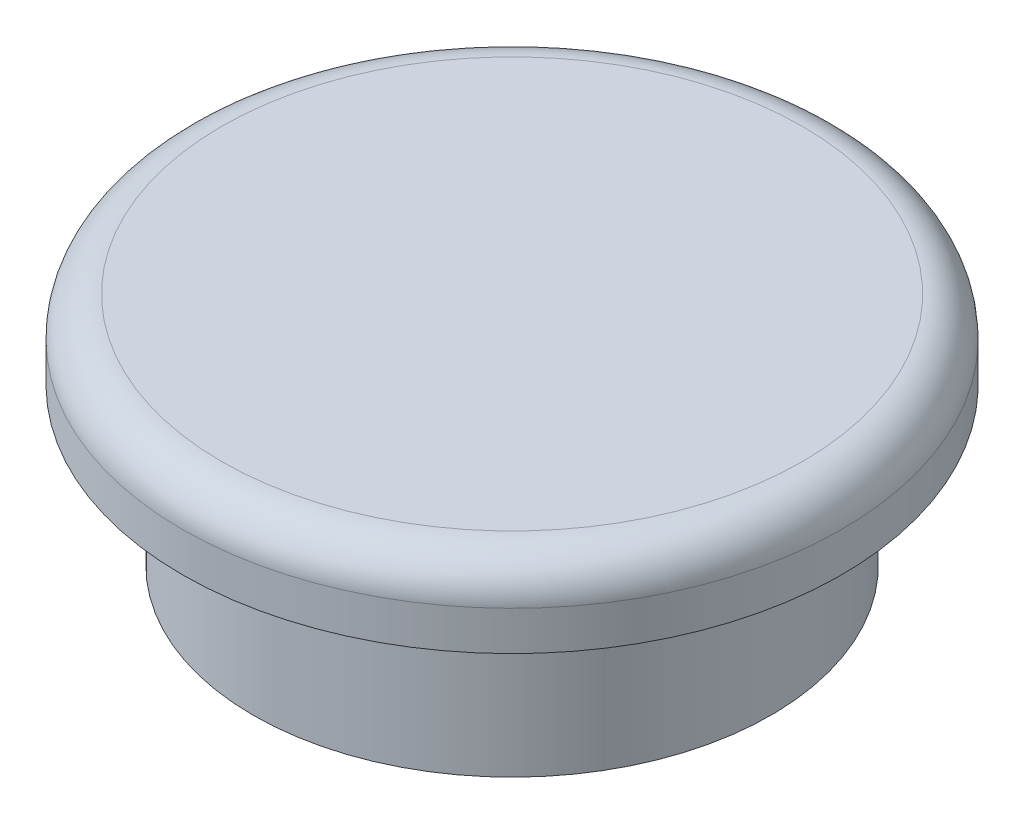
SolidWorks part; units mm, degrees
ref_plane "Front" through (0, 0, 0) normal (0, 0, 1) x (1, 0, 0)
ref_plane "Top" through (0, 0, 0) normal (0, 1, 0) x (1, 0, 0)
ref_plane "Right" through (0, 0, 0) normal (1, 0, 0) x (0, 0, -1)
sketch "Sketch1" plane through (0, 0, 0) normal (0, 1, 0) x (1, 0, 0)
  circle A0 centre (0, 0) radius 10.4775
  dimension "D1" = 20.955
extrude "Boss-Extrude1" add sketch "Sketch1" along normal blind 6.35
sketch "Sketch2" plane through (0, 6.35, 0) normal (0, 1, 0) x (1, 0, 0)
  circle A0 centre (0, 0) radius 13.335
  dimension "D1" = 26.67
extrude "Boss-Extrude2" add sketch "Sketch2" along normal blind 3.175
fillet "Fillet1" radius 1.5875 1 edges at (0, 9.525, 13.335)
